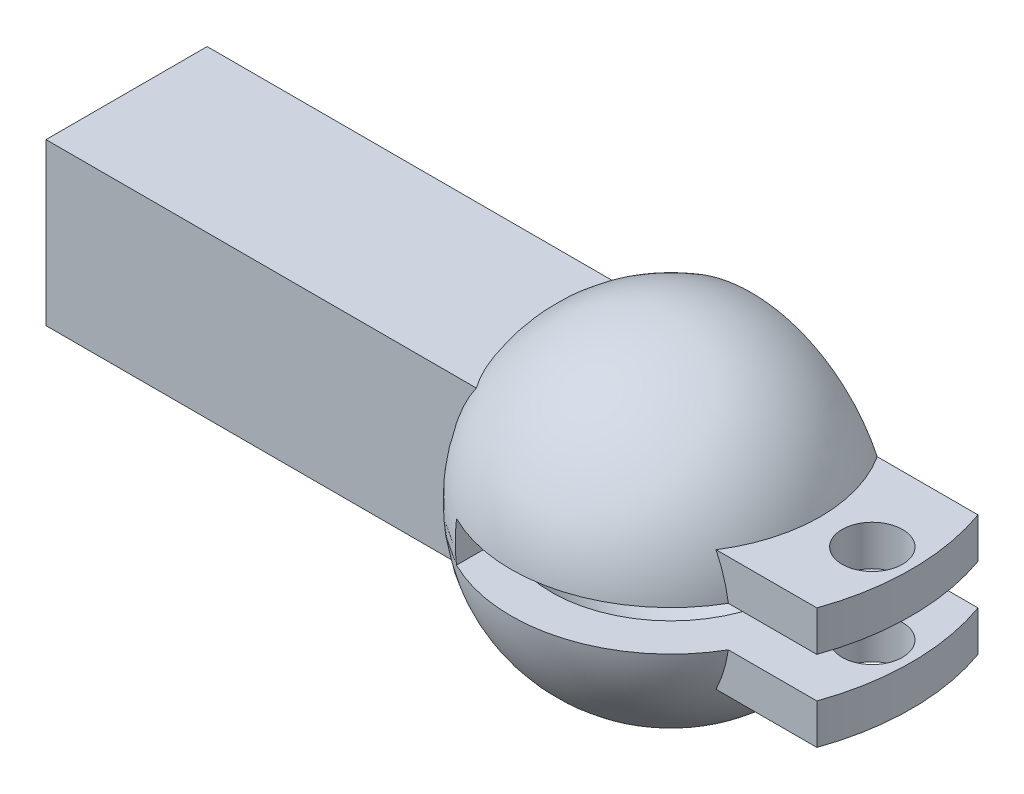
SolidWorks part; units mm, degrees
ref_plane "Plano frontal" through (0, 0, 0) normal (0, 0, 1) x (1, 0, 0)
ref_plane "Plano superior" through (0, 0, 0) normal (0, 1, 0) x (1, 0, 0)
ref_plane "Plano direito" through (0, 0, 0) normal (1, 0, 0) x (0, 0, -1)
sketch "Esboço1" plane through (0, 0, 0) normal (0, 0, 1) x (1, 0, 0)
  line L0 (29.5197, 0) -> (-29.5197, 0)
  line L1 (-29.5197, 32.3284) -> (-29.5197, 0)
  line L2 (24.146, 8) -> (-21.5197, 8)
  line L3 (-21.5197, 32.3284) -> (-21.5197, 8)
  line L4 (-29.5197, 32.3284) -> (-21.5197, 32.3284)
  line L5 (40.5144, 0) -> (48.5144, 0)
  arc A0 (40.5144, 0) -> (29.5197, 0) centre (35.017, 0) ccw
  arc A1 (48.5144, 0) -> (24.146, 8) centre (35.017, 0) ccw
  dimension "D1" = 8
extrude "Ressalto-extrusão1" add sketch "Esboço1" along normal blind 4 contours L5 A1 L2 L3 L4 L1 L0 A0
sketch "Esboço33" plane through (0, 0, 4) normal (0, 0, 1) x (1, 0, 0)
  line L6 (40.5144, 0) -> (48.5144, 0)
  line L7 (24.146, 8) -> (-21.5197, 8)
  line L8 (-21.5197, 8) -> (-21.5197, 32.3284)
  line L9 (-21.5197, 32.3284) -> (-29.5197, 32.3284)
  line L10 (-29.5197, 32.3284) -> (-29.5197, 0)
  line L11 (-29.5197, 0) -> (29.5197, 0)
  line L13 (-21.5197, 8) -> (-29.5197, 8)
  line L14 (-21.5197, 8) -> (-21.5197, 32.3284)
  line L15 (-21.5197, 32.3284) -> (-29.5197, 32.3284)
  line L16 (-29.5197, 32.3284) -> (-29.5197, 8)
  arc A2 (48.5144, 0) -> (24.146, 8) centre (35.017, 0) ccw
  arc A3 (40.5144, 0) -> (29.5197, 0) centre (35.017, 0) ccw
  dimension "D1" = 0
extrude "Corte-extrusão20" cut sketch "Esboço33" against normal through all
sketch "Esboço34" plane through (0, 0, 4) normal (0, 0, 1) x (1, 0, 0)
  line L0 (21.5197, 0) -> (21.5197, 8)
  line L1 (24.146, 8) -> (-29.5197, 8) construction
  line L2 (24.146, 8) -> (21.5197, 8)
  line L4 (24.146, 8) -> (-29.5197, 8)
  line L5 (-29.5197, 8) -> (-29.5197, 0)
  line L6 (-29.5197, 0) -> (29.5197, 0)
  line L7 (40.5144, 0) -> (48.5144, 0)
  line L10 (21.5197, 0) -> (29.5197, 0)
  line L11 (40.5144, 0) -> (48.5144, 0)
  arc A2 (40.5144, 0) -> (29.5197, 0) centre (35.017, 0) ccw
  arc A3 (48.5144, 0) -> (24.146, 8) centre (35.017, 0) ccw
  arc A4 (40.5144, 0) -> (29.5197, 0) centre (35.017, 0) ccw
  arc A5 (48.5144, 0) -> (24.146, 8) centre (35.017, 0) ccw
  dimension "D1" = 0
extrude "Corte-extrusão22" cut sketch "Esboço34" against normal through all
sketch "Esboço36" plane through (0, 0, 4) normal (0, 0, 1) x (1, 0, 0)
  line L0 (27.0197, -2) -> (27.0197, -4)
  line L2 (27.0197, -2) -> (27.0197, 10) construction
  line L3 (27.0197, 12) -> (27.0197, 10)
  line L4 (27.0197, 10) -> (27.0197, 12)
  arc A0 (27.0197, 10) -> (27.0197, -2) centre (27.0197, 4) ccw
  arc A1 (27.0197, 12) -> (27.0197, -4) centre (27.0197, 4) ccw
  dimension "D1" = 6
revolve "Revolução1" add sketch "Esboço36" angle 360 about L2
sketch "Esboço37" plane through (0, 0, 4) normal (0, 0, 1) x (1, 0, 0)
  line L0 (21.3628, 0) -> (21.3628, 8)
  line L1 (-29.5197, 0) -> (20.0915, 0)
  line L2 (-29.5197, 0) -> (-29.5197, 8)
  line L3 (-29.5197, 8) -> (20.0915, 8)
  line L7 (-29.5197, 0) -> (21.3628, 0)
  line L8 (-29.5197, 8) -> (-29.5197, 0)
  line L9 (21.3628, 8) -> (-29.5197, 8)
  line L10 (-29.5197, 0) -> (21.3628, 0)
  line L11 (-29.5197, 8) -> (-29.5197, 0)
  line L12 (21.3628, 8) -> (-29.5197, 8)
  arc A1 (21.3628, 8) -> (21.3628, 0) centre (27.0197, 4) ccw
  line M1 (-29.5197, 0) -> (20.0915, 0)
  arc M2 (20.0915, 0) -> (20.0915, 8) centre (27.0197, 4) cw
  line M3 (20.0915, 8) -> (-29.5197, 8)
  line M4 (-29.5197, 8) -> (-29.5197, 0)
  dimension "D1" = 0
extrude "Ressalto-extrusão14" add sketch "Esboço37" along normal blind 4 contours M4 M1 M2 M3 | L0 L12 L10 M2
sketch "Esboço38" plane through (0, 0, 0) normal (0, 0, -1) x (-1, 0, 0)
  circle A3 centre (-27.0197, 4) radius 7
  dimension "D1" = 14
extrude "Corte-extrusão23" cut sketch "Esboço38" along normal through all
sketch "Esboço39" plane through (0, 0, 8) normal (0, 0, 1) x (1, 0, 0)
  line L0 (0, 0) -> (0, 8)
  line L1 (21.3628, 8) -> (-29.5197, 8) construction
  line L5 (21.3628, 8) -> (-29.5197, 8)
  line L6 (-29.5197, 8) -> (-29.5197, 0)
  line L7 (-29.5197, 0) -> (21.3628, 0)
  line L8 (0, 8) -> (-29.5197, 8)
  line L9 (-29.5197, 8) -> (-29.5197, 0)
  line L10 (-29.5197, 0) -> (0, 0)
  arc A1 (21.3628, 8) -> (21.3628, 0) centre (27.0197, 4) ccw
  dimension "D1" = 0
extrude "Corte-extrusão24" cut sketch "Esboço39" against normal through all
sketch "Esboço40" plane through (0, 0, 0) normal (0, 0, -1) x (-1, 0, 0)
  line L0 (-23.4862, 4) -> (-35.0197, 4) construction
  line L1 (-23.4862, 5) -> (-35.0197, 5)
  line L2 (-23.4862, 3) -> (-35.0197, 3)
  line L3 (-35.0197, 3) -> (-35.0197, 5)
  line L4 (-23.4862, 5) -> (-23.4862, 3)
  line L5 (-20.0915, 5) -> (-35.0197, 5) construction
  line L6 (-20.0915, 4) -> (-35.0197, 4) construction
  line L7 (-20.0915, 3) -> (-35.0197, 3) construction
  arc A1 (-20.0915, 8) -> (-20.0915, 0) centre (-27.0197, 4) ccw construction
  dimension "D1" = 1
  dimension "D2" = 1
extrude "Corte-extrusão25" cut sketch "Esboço40" against normal through all and the other way through all
sketch "Esboço41" plane through (21.5197, 0, 0) normal (1, 0, 0) x (0, 0, -1)
  line L1 (-4, 6.3979) -> (-4, 1.6021)
  line L2 (-4, 6.3979) -> (-4, 1.6021)
  arc A1 (-4, 1.6021) -> (-4, 6.3979) centre (-4, 4) ccw
  arc A2 (-4, 1.6021) -> (-4, 6.3979) centre (-4, 4) ccw
  dimension "D1" = 0
extrude "Corte-extrusão26" cut sketch "Esboço41" against normal up to surface (0.1569 mm away) up to face at (21.3628, 4, 5)
sketch "Esboço42" plane through (0, 8, 0) normal (0, 1, 0) x (1, 0, 0)
  line L3 (32.5978, 0) -> (38.2668, 0)
  line L5 (32.5978, -8) -> (38.2668, -8)
  arc A2 (38.2668, -8) -> (38.2668, 0) centre (27.0197, -4) ccw
  arc A5 (32.5978, -8) -> (32.5978, 0) centre (27.0197, -4) ccw
extrude "Ressalto-extrusão15" add sketch "Esboço42" against normal blind 2 from offset 1 offset against normal yes
sketch "Esboço43" plane through (0, 5, 0) normal (0, -1, 0) x (1, 0, 0)
  line L2 (38.2668, 8) -> (33.2647, 8)
  line L3 (33.2647, 0) -> (38.2668, 0)
  line L4 (38.2668, 8) -> (33.2647, 8)
  line L5 (33.2647, 0) -> (38.2668, 0)
  arc A2 (33.2647, 0) -> (33.2647, 8) centre (27.0197, 4) ccw
  arc A3 (38.2668, 0) -> (38.2668, 8) centre (27.0197, 4) ccw
  arc A4 (33.2647, 0) -> (33.2647, 8) centre (27.0197, 4) ccw
  arc A5 (38.2668, 0) -> (38.2668, 8) centre (27.0197, 4) ccw
  dimension "D1" = 0
extrude "Ressalto-extrusão16" add sketch "Esboço43" along normal blind 2 from offset 2
sketch "Esboço44" plane through (0, 7, 0) normal (0, 1, 0) x (1, 0, 0)
  circle A0 centre (37.0197, -4) radius 1.5
  arc A1 (38.2668, -8) -> (38.2668, 0) centre (27.0197, -4) ccw construction
  dimension "D1" = 3
  dimension "D2" = 10
extrude "Corte-extrusão27" cut sketch "Esboço44" against normal through all and the other way through all contours A0
